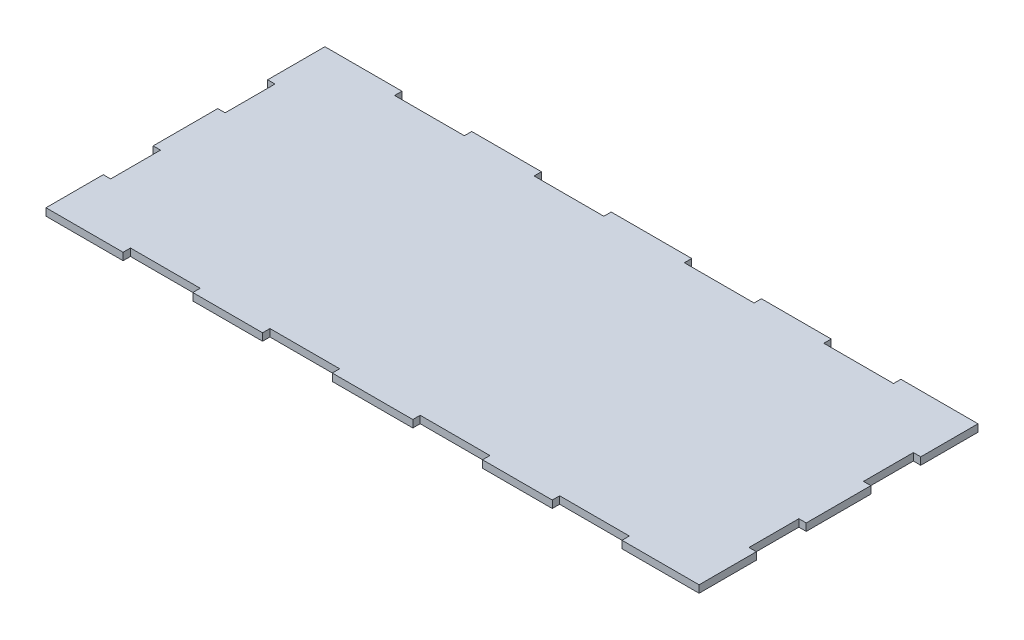
SolidWorks part; units mm, degrees
ref_plane "Front" through (0, 0, 0) normal (0, 0, 1) x (1, 0, 0)
ref_plane "Top" through (0, 0, 0) normal (0, 1, 0) x (1, 0, 0)
ref_plane "Right" through (0, 0, 0) normal (1, 0, 0) x (0, 0, -1)
sketch "Croquis1" plane through (0, 0, 0) normal (0, 1, 0) x (1, 0, 0)
  line L0 (0, 0) -> (0, 113.6) construction
  line L1 (3, 113.6) -> (31.4, 113.6)
  line L3 (266, 0) -> (0, 0) construction
  line L4 (0, 0) -> (0, 3)
  line L5 (0, 3) -> (0, 23.32)
  line L6 (0, 23.32) -> (3, 23.32)
  line L7 (3, 23.32) -> (3, 43.64)
  line L8 (0, 56.8) -> (260, 56.8) construction
  line L9 (3, 43.64) -> (0, 43.64)
  line L10 (3, 69.96) -> (0, 69.96)
  line L11 (3, 90.28) -> (3, 69.96)
  line L12 (0, 90.28) -> (3, 90.28)
  line L13 (0, 110.6) -> (0, 90.28)
  line L14 (0, 113.6) -> (0, 110.6)
  line L15 (0, 43.64) -> (0, 69.96)
  line L16 (133, 107.6) -> (133, 0) construction
  line L17 (266, 0) -> (266, 113.6) construction
  line L18 (266, 43.64) -> (266, 69.96)
  line L19 (31.4, 113.6) -> (31.4, 110.6)
  line L20 (266, 110.6) -> (266, 90.28)
  line L21 (266, 90.28) -> (263, 90.28)
  line L22 (263, 90.28) -> (263, 69.96)
  line L23 (263, 69.96) -> (266, 69.96)
  line L24 (263, 43.64) -> (266, 43.64)
  line L25 (263, 23.32) -> (263, 43.64)
  line L26 (266, 23.32) -> (263, 23.32)
  line L27 (266, 3) -> (266, 23.32)
  line L28 (266, 0) -> (266, 3)
  line L29 (31.4, 110.6) -> (59.8, 110.6)
  line L30 (59.8, 110.6) -> (59.8, 113.6)
  line L31 (0, 113.6) -> (3, 113.6)
  line L32 (59.8, 113.6) -> (88.2, 113.6)
  line L33 (88.2, 113.6) -> (88.2, 110.6)
  line L34 (88.2, 110.6) -> (116.6, 110.6)
  line L35 (116.6, 110.6) -> (116.6, 113.6)
  line L36 (149.4, 110.6) -> (149.4, 113.6)
  line L37 (177.8, 110.6) -> (149.4, 110.6)
  line L38 (177.8, 113.6) -> (177.8, 110.6)
  line L39 (206.2, 113.6) -> (177.8, 113.6)
  line L40 (206.2, 110.6) -> (206.2, 113.6)
  line L41 (234.6, 110.6) -> (206.2, 110.6)
  line L42 (234.6, 113.6) -> (234.6, 110.6)
  line L43 (263, 113.6) -> (234.6, 113.6)
  line L44 (116.6, 113.6) -> (149.4, 113.6)
  line L45 (266, 0) -> (263, 0)
  line L46 (266, 113.6) -> (263, 113.6)
  line L47 (0, 0) -> (3, 0)
  line L48 (266, 113.6) -> (266, 110.6)
  line L49 (3, 0) -> (31.4, 0)
  line L50 (116.6, 0) -> (149.4, 0)
  line L51 (263, 0) -> (234.6, 0)
  line L52 (234.6, 0) -> (234.6, 3)
  line L53 (234.6, 3) -> (206.2, 3)
  line L54 (206.2, 3) -> (206.2, 0)
  line L55 (206.2, 0) -> (177.8, 0)
  line L56 (177.8, 0) -> (177.8, 3)
  line L57 (177.8, 3) -> (149.4, 3)
  line L58 (149.4, 3) -> (149.4, 0)
  line L59 (116.6, 3) -> (116.6, 0)
  line L60 (88.2, 3) -> (116.6, 3)
  line L61 (88.2, 0) -> (88.2, 3)
  line L62 (59.8, 0) -> (88.2, 0)
  line L63 (59.8, 3) -> (59.8, 0)
  line L64 (31.4, 3) -> (59.8, 3)
  line L65 (31.4, 0) -> (31.4, 3)
  dimension "D1" = 113.6
  dimension "D2" = 266
  dimension "D3" = 3
  dimension "D4" = 20.32
  dimension "D6" = 28.4
  dimension "D7" = 3
extrude "Saliente-Extruir1" add sketch "Croquis1" along normal blind 3
